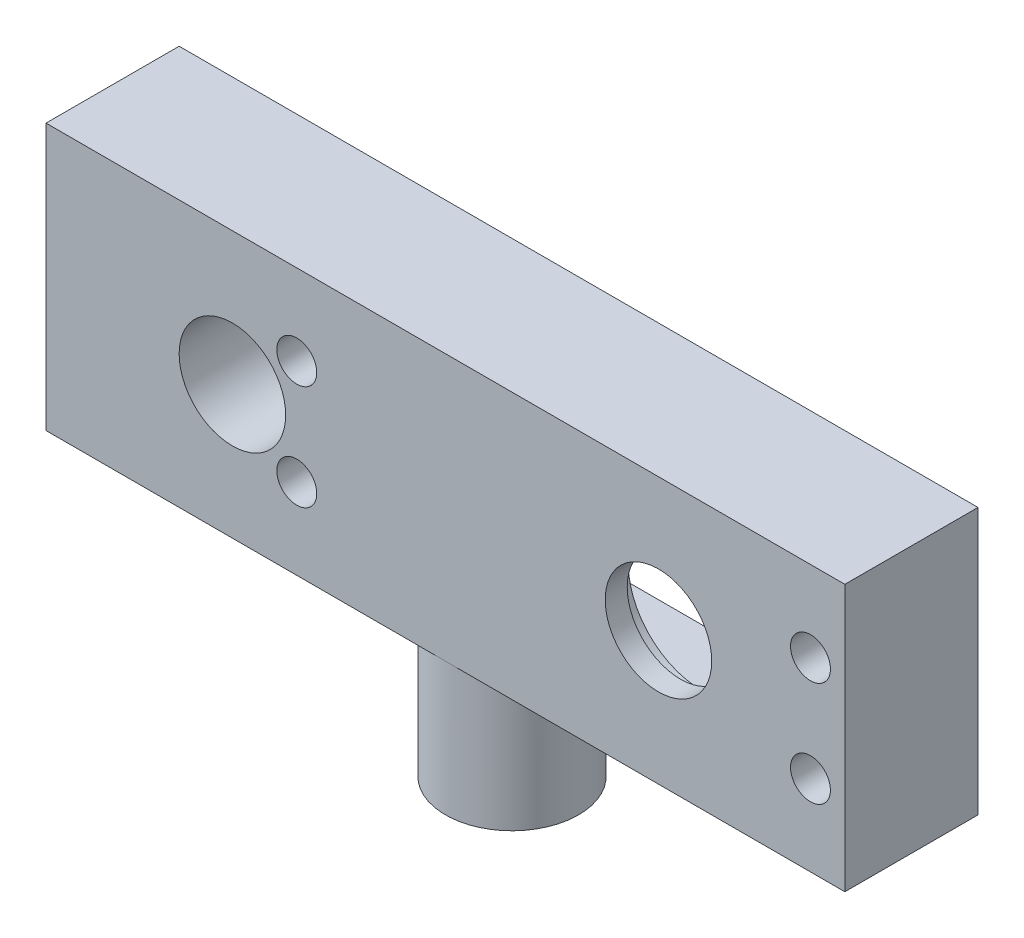
SolidWorks part; units mm, degrees
ref_plane "Front Plane" through (0, 0, 0) normal (0, 0, 1) x (1, 0, 0)
ref_plane "Top Plane" through (0, 0, 0) normal (0, 1, 0) x (1, 0, 0)
ref_plane "Right Plane" through (0, 0, 0) normal (1, 0, 0) x (0, 0, -1)
sketch "Sketch1" plane through (0, 0, 0) normal (0, 0, 1) x (1, 0, 0)
  line L1 (-38.1, -12.7) -> (38.1, -12.7)
  line L2 (-38.1, -12.7) -> (-38.1, 12.7)
  line L3 (-38.1, 12.7) -> (38.1, 12.7)
  line L4 (38.1, -12.7) -> (38.1, 12.7)
  line L5 (-38.1, -12.7) -> (38.1, 12.7) construction
  line L6 (-38.1, 12.7) -> (38.1, -12.7) construction
  point P0 (0, 0)
  dimension "D1" = 25.4
  dimension "D2" = 76.2
extrude "Boss-Extrude1" add sketch "Sketch1" along normal blind 12.7
sketch "Sketch2" plane through (0, 0, 12.7) normal (0, 0, 1) x (1, 0, 0)
  line L0 (0, 12.7) -> (0, -12.7) construction
  line L1 (38.1, 12.7) -> (-38.1, 12.7) construction
  line L2 (-38.1, -12.7) -> (38.1, -12.7) construction
  line L3 (-38.1, 0) -> (38.1, 0) construction
  line L4 (-38.1, 12.7) -> (-38.1, -12.7) construction
  line L5 (38.1, -12.7) -> (38.1, 12.7) construction
  circle A0 centre (20.32, 0) radius 5.08
  circle A1 centre (-20.32, 0) radius 5.08
  point P14 (20.3392, 0)
  dimension "D1" = 10.16
  dimension "D2" = 20.32
extrude "Cut-Extrude1" cut sketch "Sketch2" against normal through all
sketch "Sketch3" plane through (0, 0, 12.7) normal (0, 0, 1) x (1, 0, 0)
  line L0 (-38.1, 0) -> (38.1, 0) construction
  line L1 (-38.1, 12.7) -> (-38.1, -12.7) construction
  line L2 (38.1, -12.7) -> (38.1, 12.7) construction
  circle A0 centre (34.8201, 5) radius 1.905
  circle A1 centre (-14.1798, 5) radius 1.905
  circle A2 centre (20.32, 0) radius 5.08 construction
  circle A3 centre (34.8201, -5) radius 1.905
  circle A4 centre (-14.1798, -5) radius 1.905
  point P12 (-19.2819, 5)
  dimension "D2" = 3.81
  dimension "D3" = 14.5001
  dimension "D4" = 10
  dimension "D1" = 48.9999
extrude "Cut-Extrude2" cut sketch "Sketch3" against normal through all
sketch "Sketch4" plane through (0, 0, 0) normal (0, 0, -1) x (-1, 0, 0)
  line L0 (-10.3201, 12.7) -> (-10.3201, -12.7) construction
  line L1 (-30.6401, -10.16) -> (9.9999, -10.16)
  line L2 (-30.6401, -10.16) -> (-30.6401, 10.16)
  line L3 (-30.6401, 10.16) -> (9.9999, 10.16)
  line L4 (9.9999, -10.16) -> (9.9999, 10.16)
  line L5 (-30.6401, -10.16) -> (9.9999, 10.16) construction
  line L6 (-30.6401, 10.16) -> (9.9999, -10.16) construction
  line L7 (-38.1, 12.7) -> (38.1, 12.7) construction
  line L8 (38.1, -12.7) -> (-38.1, -12.7) construction
  line L9 (-38.1, 0) -> (38.1, 0) construction
  line L10 (-30.6401, 1.27) -> (-36.3441, 1.27)
  line L11 (-30.6401, 1.27) -> (-30.6401, -1.27)
  line L12 (-30.6401, -1.27) -> (-36.3441, -1.27)
  line L13 (-36.3441, 1.27) -> (-36.3441, -1.27)
  line L14 (-38.1, -12.7) -> (-38.1, 12.7) construction
  line L15 (38.1, 12.7) -> (38.1, -12.7) construction
  line L16 (-36.3441, 12.7) -> (-36.3441, -12.7) construction
  line L17 (-34.8201, 3.095) -> (-34.8201, -3.095) construction
  line L18 (9.9999, -1.27) -> (15.7038, -1.27)
  line L19 (15.7038, 1.27) -> (15.7038, -1.27)
  line L20 (9.9999, 1.27) -> (15.7038, 1.27)
  line L21 (9.9999, 1.27) -> (9.9999, -1.27)
  circle A0 centre (-34.8201, 5) radius 1.905 construction
  circle A1 centre (14.1798, 5) radius 1.905 construction
  circle A2 centre (-34.8201, -5) radius 1.905 construction
  point P0 (-10.3201, 0)
  point P25 (-36.3441, 0)
  point P26 (-34.8201, -3.857)
  point P31 (-35.9631, 5)
  point P39 (0, 0)
  point P40 (-35.9631, 4.9897)
  point P41 (-36.3441, -12.7)
  point P42 (-36.3441, 12.7)
  dimension "D1" = 40.64
  dimension "D2" = 20.32
  dimension "D3" = 2.54
  dimension "D4" = 1.524
extrude "Cut-Extrude3" cut sketch "Sketch4" against normal blind 8.5999 contours L18 L19 L20 L21 | L2 L1 L4 L3 | L11 L10 L13 L12
sketch "Sketch5" plane through (0, 0, 8.5999) normal (0, 0, -1) x (-1, 0, 0)
  circle A0 centre (-20.32, 0) radius 6.985
  dimension "D1" = 13.97
extrude "Cut-Extrude4" cut sketch "Sketch5" against normal blind 2
sketch "Sketch9" plane through (0, -12.7, 0) normal (0, -1, 0) x (1, 0, 0)
  line L0 (0, 12.7) -> (0, 0) construction
  line L1 (-38.1, 12.7) -> (38.1, 12.7) construction
  circle A0 centre (0, 6.35) radius 6.35
extrude "Boss-Extrude3" add sketch "Sketch9" along normal blind 12.7
sketch "Sketch7" plane through (0, -25.4, 0) normal (0, -1, 0) x (1, 0, 0)
  line L0 (0, 12.7) -> (0, 0) construction
  line L3 (-6.35, 6.35) -> (6.35, 6.35) construction
  circle A0 centre (0, 6.35) radius 3.175
  arc A1 (0, 0) -> (0, 12.7) centre (0, 6.35) ccw construction
  point P2 (6.35, 6.35)
  point P8 (0, 0)
  point P10 (12.7, 6.35)
  point P14 (0, 6.35)
  dimension "D1" = 6.35
extrude "Cut-Extrude5" cut sketch "Sketch7" against normal up to surface (12.7 mm away) up to face at (20.6375, -12.7, 6.35)
